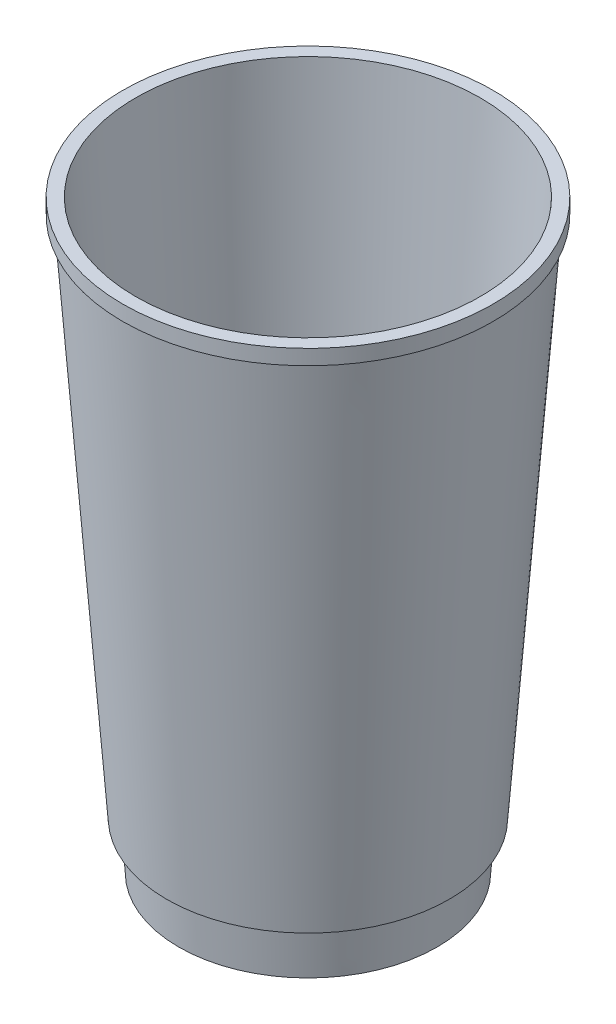
SolidWorks part; units mm, degrees
ref_plane "前视基准面" through (0, 0, 0) normal (0, 0, 1) x (1, 0, 0)
ref_plane "上视基准面" through (0, 0, 0) normal (0, 1, 0) x (1, 0, 0)
ref_plane "右视基准面" through (0, 0, 0) normal (1, 0, 0) x (0, 0, -1)
sketch "草图1" plane through (0, 0, 0) normal (0, 1, 0) x (1, 0, 0)
  circle A0 centre (0, 0) radius 30
  dimension "D1" = 60
ref_plane "基准面4" through (0, 11, 0) normal (0, 1, 0) x (1, 0, 0)
sketch "草图2" plane through (0, 11, 0) normal (0, 1, 0) x (1, 0, 0)
  circle A0 centre (0, 0) radius 30.775
  dimension "D1" = 61.55
sketch "草图3" plane through (0, 11, 0) normal (0, 1, 0) x (1, 0, 0)
  circle A0 centre (0, 0) radius 32.8
  dimension "D1" = 65.6
ref_plane "基准面5" through (0, 132.3, 0) normal (0, 1, 0) x (1, 0, 0)
sketch "草图4" plane through (0, 132.3, 0) normal (0, 1, 0) x (1, 0, 0)
  circle A0 centre (0, 0) radius 41.75
  dimension "D1" = 83.5
sketch "草图5" plane through (0, 132.3, 0) normal (0, 1, 0) x (1, 0, 0)
  circle A0 centre (0, 0) radius 43
  dimension "D1" = 86
ref_plane "基准面6" through (0, 135.8, 0) normal (0, 1, 0) x (1, 0, 0)
sketch "草图6" plane through (0, 135.8, 0) normal (0, 1, 0) x (1, 0, 0)
  circle A0 centre (0, 0) radius 43
  dimension "D1" = 86
loft "放样2" add profiles "草图5", "草图6"
loft "放样3" add profiles "草图3", "草图4"
loft "放样4" add profiles "草图2", "草图1"
sketch "草图11" plane through (0, 0, 0) normal (0, 1, 0) x (1, 0, 0)
  circle A2 centre (0, 0) radius 29
  circle A3 centre (0, 0) radius 29
  dimension "D1" = 1
sketch "草图12" plane through (0, 11, 0) normal (0, 1, 0) x (1, 0, 0)
  circle A2 centre (0, 0) radius 29.775
  circle A3 centre (0, 0) radius 29.775
  dimension "D1" = 1
loft "切除-放样1" cut profiles "草图11", "草图12"
ref_plane "基准面8" through (0, 12, 0) normal (0, 1, 0) x (1, 0, 0)
sketch "草图13" plane through (0, 135.8, 0) normal (0, 1, 0) x (1, 0, 0)
  circle A2 centre (0, 0) radius 40
  circle A3 centre (0, 0) radius 40
  dimension "D1" = 3
sketch "草图14" plane through (0, 12, 0) normal (0, 1, 0) x (1, 0, 0)
  circle A2 centre (0, 0) radius 31.8
  circle A3 centre (0, 0) radius 31.8
  dimension "D1" = 1
loft "切除-放样2" cut profiles "草图13", "草图14"
